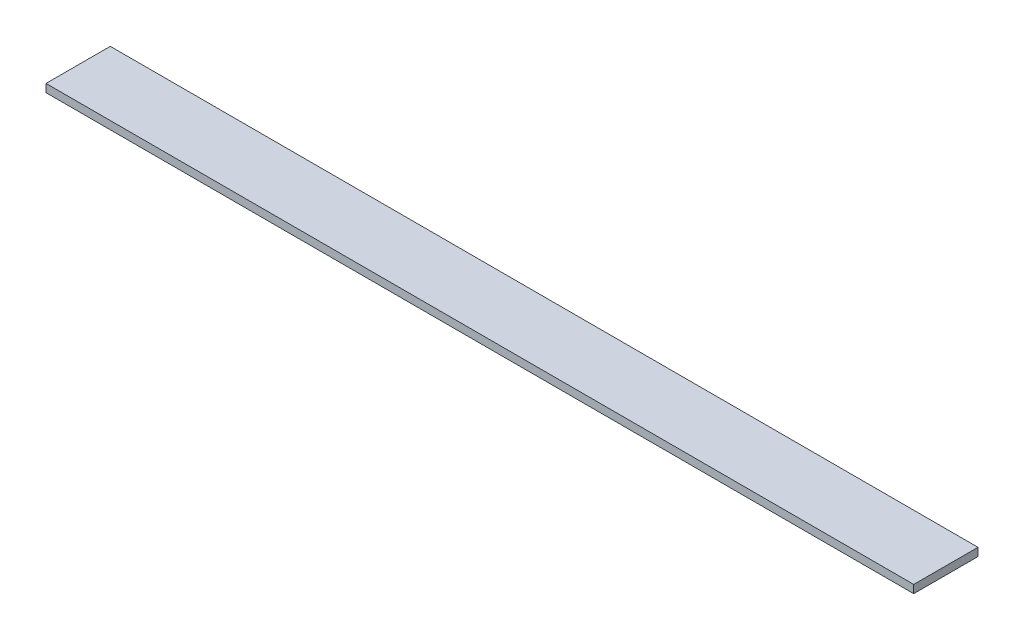
SolidWorks part; units mm, degrees
material "ABS PC"
ref_plane "Front Plane" through (0, 0, 0) normal (0, 0, 1) x (1, 0, 0)
ref_plane "Top Plane" through (0, 0, 0) normal (0, 1, 0) x (1, 0, 0)
ref_plane "Right Plane" through (0, 0, 0) normal (1, 0, 0) x (0, 0, -1)
sketch "Sketch1" plane through (0, 0, 0) normal (0, 1, 0) x (1, 0, 0)
  line L1 (-74.7636, 1.1273) -> (33.2364, 1.1273)
  line L2 (-74.7636, 1.1273) -> (-74.7636, -6.8727)
  line L3 (-74.7636, -6.8727) -> (33.2364, -6.8727)
  line L4 (33.2364, 1.1273) -> (33.2364, -6.8727)
  dimension "D1" = 8
  dimension "D2" = 108
extrude "Boss-Extrude1" add sketch "Sketch1" along normal blind 1
